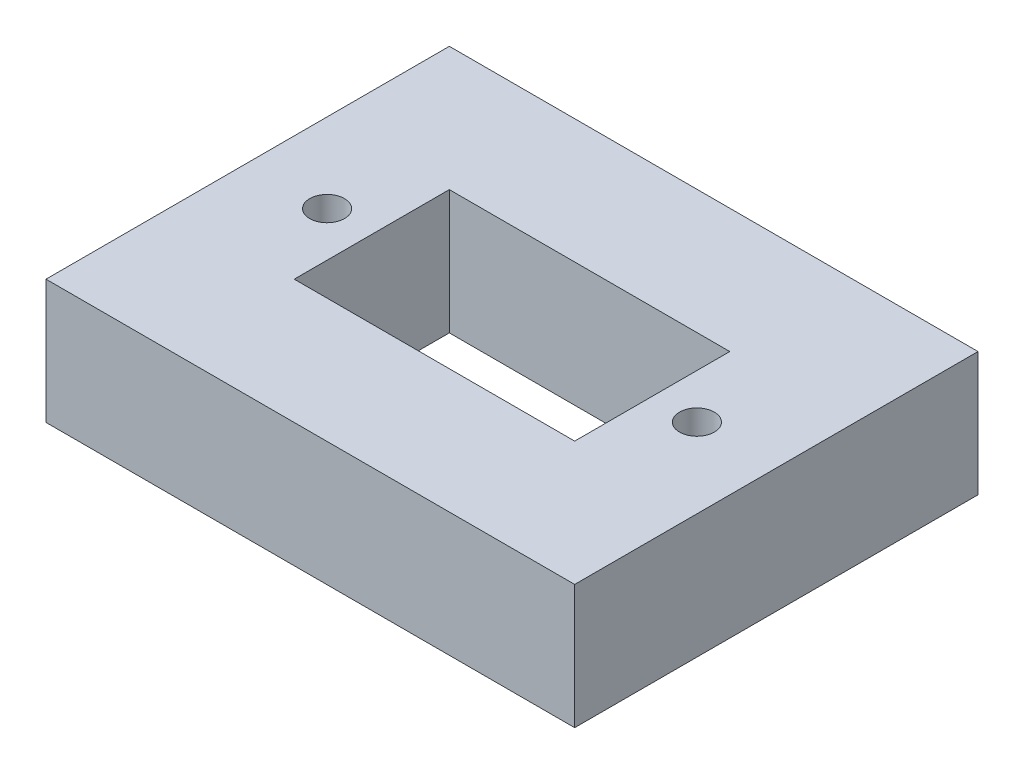
SolidWorks part; units mm, degrees
ref_plane "Front Plane" through (0, 0, 0) normal (0, 0, 1) x (1, 0, 0)
ref_plane "Top Plane" through (0, 0, 0) normal (0, 1, 0) x (1, 0, 0)
ref_plane "Right Plane" through (0, 0, 0) normal (1, 0, 0) x (0, 0, -1)
sketch "Sketch1" plane through (0, 0, 0) normal (0, 1, 0) x (1, 0, 0)
  line L0 (21.3, -16.25) -> (21.3, 16.25)
  line L1 (-11.3, -6.25) -> (11.3, -6.25)
  line L2 (-11.3, -6.25) -> (-11.3, 6.25)
  line L3 (-11.3, 6.25) -> (11.3, 6.25)
  line L4 (11.3, -6.25) -> (11.3, 6.25)
  line L5 (-11.3, -6.25) -> (11.3, 6.25) construction
  line L6 (-11.3, 6.25) -> (11.3, -6.25) construction
  line L7 (-21.3, 16.25) -> (21.3, 16.25)
  line L8 (-21.3, -16.25) -> (-21.3, 16.25)
  line L9 (-21.3, -16.25) -> (21.3, -16.25)
  line L10 (-21.3, 0) -> (21.3, 0) construction
  line L11 (-16.3, 16.25) -> (-16.3, -16.25) construction
  line L12 (0, 16.25) -> (0, -16.25) construction
  line L13 (16.3, 16.25) -> (16.3, -16.25) construction
  circle A0 centre (-14.9, 0) radius 1.4
  circle A1 centre (14.9, 0) radius 1.4
  point P0 (0, 0)
  dimension "D4" = 2.8
  dimension "D1" = 12.5
  dimension "D2" = 22.6
  dimension "D5" = 5
  dimension "D3" = 10
extrude "Boss-Extrude1" add sketch "Sketch1" along normal blind 10
